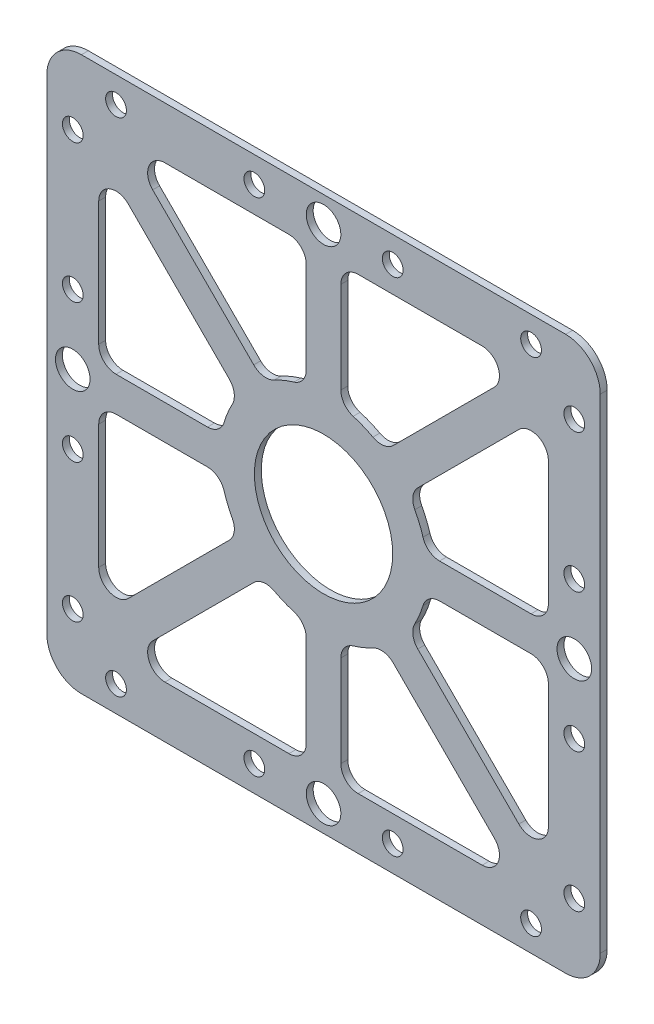
SolidWorks part; units mm, degrees
material "Fibra de vidrio-A"
ref_plane "Alzado" through (0, 0, 0) normal (0, 0, 1) x (1, 0, 0)
ref_plane "Planta" through (0, 0, 0) normal (0, 1, 0) x (1, 0, 0)
ref_plane "Vista lateral" through (0, 0, 0) normal (1, 0, 0) x (0, 0, -1)
sketch "Croquis1" plane through (0, 0, 0) normal (0, 0, 1) x (1, 0, 0)
  line L1 (-35, -40) -> (35, -40)
  line L2 (-40, -35) -> (-40, 35)
  line L3 (-35, 40) -> (35, 40)
  line L4 (40, -35) -> (40, 35)
  line L5 (-40, -40) -> (40, 40) construction
  line L6 (-40, 40) -> (40, -40) construction
  arc A0 (35, 40) -> (40, 35) centre (35, 35) cw
  arc A1 (35, -40) -> (40, -35) centre (35, -35) ccw
  arc A2 (-35, -40) -> (-40, -35) centre (-35, -35) cw
  arc A3 (-40, 35) -> (-35, 40) centre (-35, 35) cw
  point P0 (0, 0)
  dimension "D2" = 5
  dimension "D1" = 80
extrude "Saliente-Extruir1" add sketch "Croquis1" along normal blind 1
sketch "Croquis2" plane through (0, 0, 1) normal (0, 0, 1) x (1, 0, 0)
  line L0 (0, 0) -> (0, 40) construction
  line L1 (35, 40) -> (-35, 40) construction
  line L2 (0, 0) -> (40, 0) construction
  line L3 (40, -35) -> (40, 35) construction
  line L4 (2.5, 16.7705) -> (2.5, 30)
  line L5 (0, 0) -> (38.5355, 38.5355) construction
  line L6 (10.0908, 13.6263) -> (24.6967, 28.2322)
  line L7 (5, 32.5) -> (22.9289, 32.5)
  line L8 (-10.0908, 13.6263) -> (-24.6967, 28.2322)
  line L9 (-5, 32.5) -> (-22.9289, 32.5)
  line L10 (-2.5, 16.7705) -> (-2.5, 30)
  line L11 (32.5, 5) -> (32.5, 22.9289)
  line L12 (16.7705, 2.5) -> (30, 2.5)
  line L13 (13.6263, 10.0908) -> (28.2322, 24.6967)
  line L14 (16.7705, -2.5) -> (30, -2.5)
  line L15 (32.5, -5) -> (32.5, -22.9289)
  line L16 (13.6263, -10.0908) -> (28.2322, -24.6967)
  line L17 (5, -32.5) -> (22.9289, -32.5)
  line L18 (2.5, -16.7705) -> (2.5, -30)
  line L19 (10.0908, -13.6263) -> (24.6967, -28.2322)
  line L20 (-2.5, -16.7705) -> (-2.5, -30)
  line L21 (-5, -32.5) -> (-22.9289, -32.5)
  line L22 (-10.0908, -13.6263) -> (-24.6967, -28.2322)
  line L23 (-32.5, -5) -> (-32.5, -22.9289)
  line L24 (-16.7705, -2.5) -> (-30, -2.5)
  line L25 (-13.6263, -10.0908) -> (-28.2322, -24.6967)
  line L26 (-16.7705, 2.5) -> (-30, 2.5)
  line L27 (-32.5, 5) -> (-32.5, 22.9289)
  line L28 (-13.6263, 10.0908) -> (-28.2322, 24.6967)
  circle A0 centre (0, 0) radius 10
  arc A1 (7.134, 13.1949) -> (4.2857, 14.3747) centre (0, 0) ccw
  arc A2 (40, 35) -> (35, 40) centre (35, 35) ccw construction
  circle A3 centre (0, 0) radius 15 construction
  arc A4 (2.5, 16.7705) -> (4.2857, 14.3747) centre (5, 16.7705) ccw
  arc A5 (10.0908, 13.6263) -> (7.134, 13.1949) centre (8.323, 15.3941) cw
  arc A6 (24.6967, 28.2322) -> (22.9289, 32.5) centre (22.9289, 30) ccw
  arc A7 (2.5, 30) -> (5, 32.5) centre (5, 30) cw
  arc A8 (-24.6967, 28.2322) -> (-22.9289, 32.5) centre (-22.9289, 30) cw
  arc A9 (-2.5, 30) -> (-5, 32.5) centre (-5, 30) ccw
  arc A10 (-2.5, 16.7705) -> (-4.2857, 14.3747) centre (-5, 16.7705) cw
  arc A11 (-10.0908, 13.6263) -> (-7.134, 13.1949) centre (-8.323, 15.3941) ccw
  arc A12 (-7.134, 13.1949) -> (-4.2857, 14.3747) centre (0, 0) cw
  arc A13 (28.2322, 24.6967) -> (32.5, 22.9289) centre (30, 22.9289) cw
  arc A14 (30, 2.5) -> (32.5, 5) centre (30, 5) ccw
  arc A15 (16.7705, 2.5) -> (14.3747, 4.2857) centre (16.7705, 5) cw
  arc A16 (13.1949, 7.134) -> (14.3747, 4.2857) centre (0, 0) cw
  arc A17 (13.6263, 10.0908) -> (13.1949, 7.134) centre (15.3941, 8.323) ccw
  arc A18 (13.1949, -7.134) -> (14.3747, -4.2857) centre (0, 0) ccw
  arc A19 (13.6263, -10.0908) -> (13.1949, -7.134) centre (15.3941, -8.323) cw
  arc A20 (16.7705, -2.5) -> (14.3747, -4.2857) centre (16.7705, -5) ccw
  arc A21 (30, -2.5) -> (32.5, -5) centre (30, -5) cw
  arc A22 (28.2322, -24.6967) -> (32.5, -22.9289) centre (30, -22.9289) ccw
  arc A23 (24.6967, -28.2322) -> (22.9289, -32.5) centre (22.9289, -30) cw
  arc A24 (2.5, -30) -> (5, -32.5) centre (5, -30) ccw
  arc A25 (2.5, -16.7705) -> (4.2857, -14.3747) centre (5, -16.7705) cw
  arc A26 (7.134, -13.1949) -> (4.2857, -14.3747) centre (0, 0) cw
  arc A27 (10.0908, -13.6263) -> (7.134, -13.1949) centre (8.323, -15.3941) ccw
  arc A28 (-7.134, -13.1949) -> (-4.2857, -14.3747) centre (0, 0) ccw
  arc A29 (-10.0908, -13.6263) -> (-7.134, -13.1949) centre (-8.323, -15.3941) cw
  arc A30 (-2.5, -16.7705) -> (-4.2857, -14.3747) centre (-5, -16.7705) ccw
  arc A31 (-2.5, -30) -> (-5, -32.5) centre (-5, -30) cw
  arc A32 (-24.6967, -28.2322) -> (-22.9289, -32.5) centre (-22.9289, -30) ccw
  arc A33 (-28.2322, -24.6967) -> (-32.5, -22.9289) centre (-30, -22.9289) cw
  arc A34 (-30, -2.5) -> (-32.5, -5) centre (-30, -5) ccw
  arc A35 (-16.7705, -2.5) -> (-14.3747, -4.2857) centre (-16.7705, -5) cw
  arc A36 (-13.1949, -7.134) -> (-14.3747, -4.2857) centre (0, 0) cw
  arc A37 (-13.6263, -10.0908) -> (-13.1949, -7.134) centre (-15.3941, -8.323) ccw
  arc A38 (-13.1949, 7.134) -> (-14.3747, 4.2857) centre (0, 0) ccw
  arc A39 (-13.6263, 10.0908) -> (-13.1949, 7.134) centre (-15.3941, 8.323) cw
  arc A40 (-16.7705, 2.5) -> (-14.3747, 4.2857) centre (-16.7705, 5) ccw
  arc A41 (-30, 2.5) -> (-32.5, 5) centre (-30, 5) cw
  arc A42 (-28.2322, 24.6967) -> (-32.5, 22.9289) centre (-30, 22.9289) ccw
  point P25 (28.9645, 32.5)
  point P28 (2.5, 32.5)
  point P116 (0, 0)
  dimension "D1" = 20
  dimension "D7" = 2.5
  dimension "D2" = 5
  dimension "D3" = 7.5
  dimension "D4" = 2.5
  dimension "D5" = 5
  dimension "D8" = 4
extrude "Cortar-Extruir1" cut sketch "Croquis2" against normal through all
sketch "Croquis3" plane through (0, 0, 1) normal (0, 0, 1) x (1, 0, 0)
  line L0 (-36.25, -40) -> (-36.25, 40) construction
  line L1 (-40, 35) -> (-40, -35) construction
  line L2 (-40, 0) -> (-32.5, 0) construction
  line L3 (35, 40) -> (-35, 40) construction
  line L4 (0, -0.825) -> (0, 0.825) construction
  circle A0 centre (-36.25, 30) radius 1.5
  circle A1 centre (-36.25, 10) radius 1.5
  circle A2 centre (-36.25, -10) radius 1.5
  circle A3 centre (-36.25, -30) radius 1.5
  circle A4 centre (36.25, -30) radius 1.5
  circle A5 centre (36.25, -10) radius 1.5
  circle A6 centre (36.25, 10) radius 1.5
  circle A7 centre (36.25, 30) radius 1.5
  circle A8 centre (-36.25, 0) radius 2.5
  circle A9 centre (36.25, 0) radius 2.5
  point P8 (-36.25, 0)
  dimension "D1" = 3
  dimension "D2" = 10
  dimension "D4" = 5
  dimension "D3" = 4
extrude "Cortar-Extruir2" cut sketch "Croquis3" against normal through all
pattern_circular "MatrizC1" count 4 over 360 about axis through (0, 0, 0) along (0, 0, 1) of "Cortar-Extruir2"
